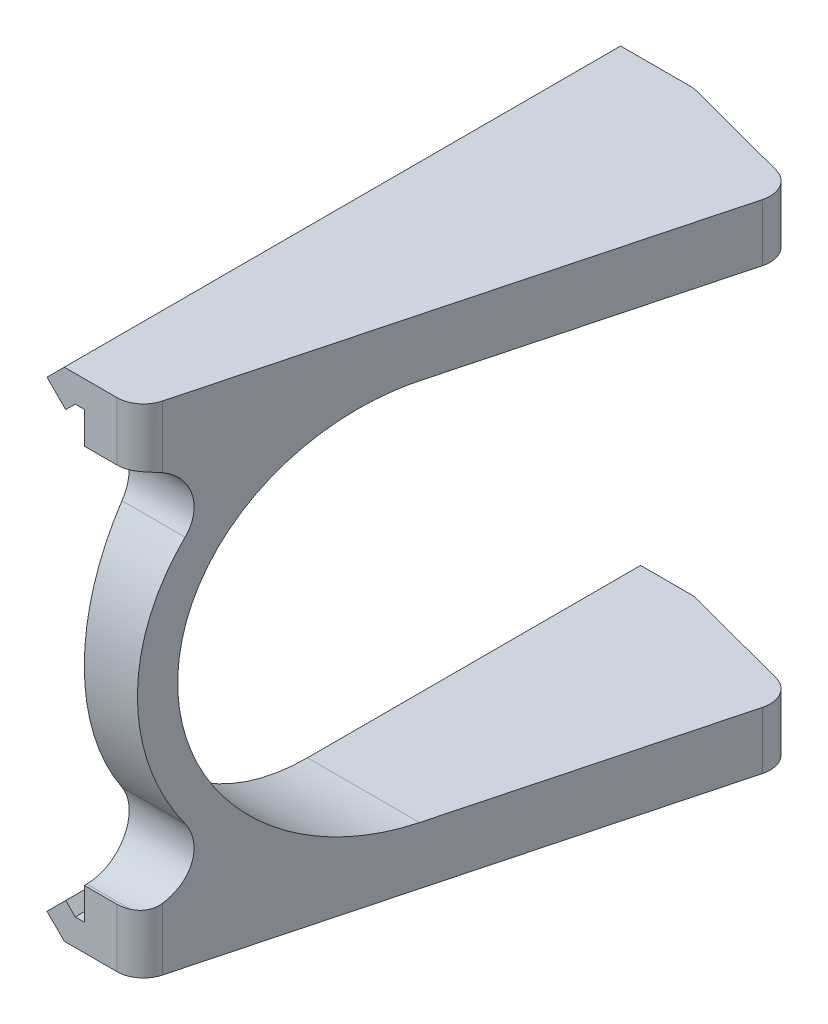
SolidWorks part; units mm, degrees
ref_plane "Front Plane" through (0, 0, 0) normal (0, 0, 1) x (1, 0, 0)
ref_plane "Top Plane" through (0, 0, 0) normal (0, 1, 0) x (1, 0, 0)
ref_plane "Right Plane" through (0, 0, 0) normal (1, 0, 0) x (0, 0, -1)
sketch "Sketch1" plane through (0, 0, 0) normal (0, 0, 1) x (1, 0, 0)
  line L0 (-68.2875, 96.7196) -> (-66.4875, 98.5196)
  line L1 (-66.4875, 98.5196) -> (-64.7875, 98.5196)
  line L2 (-64.7875, 98.5196) -> (-64.7875, 14.8821)
  line L8 (-54.7875, 9.8821) -> (-54.7875, 103.5196)
  line L9 (-54.7875, 103.5196) -> (-68.5586, 103.5196)
  line L10 (-68.5586, 103.5196) -> (-71.823, 100.2552)
  line L11 (-71.823, 100.2552) -> (-68.2875, 96.7196)
  line L12 (-64.7875, 74.7196) -> (-64.7875, 98.2196) construction
  line L13 (-66.7875, 98.2196) -> (-67.7875, 97.2196) construction
  line L14 (-66.7875, 98.2196) -> (-64.7875, 98.2196) construction
  line L15 (-67.7875, 97.2196) -> (-67.7875, 74.7196) construction
  line L16 (-64.7875, 56.7009) -> (-45.1184, 56.7009) construction
  line L17 (-71.823, 13.1466) -> (-68.2875, 16.6821)
  line L18 (-68.2875, 16.6821) -> (-66.4875, 14.8821)
  line L19 (-68.5586, 9.8821) -> (-71.823, 13.1466)
  line L20 (-54.7875, 9.8821) -> (-68.5586, 9.8821)
  line L21 (-66.4875, 14.8821) -> (-64.7875, 14.8821)
  line L22 (-66.7875, 15.1821) -> (-67.7875, 16.1821) construction
  dimension "D1" = 10
  dimension "D2" = 5
  dimension "D3" = 0.3
  dimension "D4" = 5
  dimension "D5" = 0.5
extrude "Boss-Extrude1" add sketch "Sketch1" along normal up to surface (91.9928 mm away) and the other way up to surface (12.7822 mm away)
sketch "Sketch2" plane through (0, 9.8821, 0) normal (0, 1, 0) x (1, 0, 0)
  line L0 (-54.7875, 12.7822) -> (-54.7875, -91.9928)
  line L1 (-54.7875, -91.9928) -> (-28.8809, 5.9282)
  line L2 (-28.8809, 5.9282) -> (-54.7875, 12.7822)
  dimension "D1" = 14.819
extrude "Boss-Extrude2" add sketch "Sketch2" along direction (0, -1, 0) on the side of the normal up to surface (93.6375 mm away)
sketch "Sketch3" plane through (-64.7875, 0, 0) normal (-1, 0, 0) x (0, 0, 1)
  line L0 (-12.7822, 56.7009) -> (91.9928, 56.7009) construction
  line L1 (-12.7822, 14.8821) -> (-12.7822, 98.5196) construction
  line L2 (91.9928, 14.8821) -> (91.9928, 98.5196) construction
  line L3 (66.6574, 20.6821) -> (52.8488, 20.6821) construction
  line L4 (49.974, 92.7196) -> (-12.7822, 92.7196)
  line L5 (-12.7822, 92.7196) -> (-12.7822, 20.6821)
  line L6 (-12.7822, 20.6821) -> (49.974, 20.6821)
  line L8 (85.9928, 52.4105) -> (85.9928, 59.8544) construction
  line L9 (91.5431, 20.8821) -> (97.1802, 20.8821)
  line L10 (97.1802, 20.8821) -> (97.1802, 92.5196)
  line L11 (91.9928, 14.8821) -> (-12.7822, 14.8821) construction
  line L13 (91.5431, 92.5196) -> (97.1802, 92.5196)
  arc A0 (49.974, 20.6821) -> (49.974, 92.7196) centre (49.974, 56.7009) ccw
  arc A1 (84.8946, 80.0703) -> (84.8946, 33.3315) centre (49.974, 56.7009) cw
  arc A2 (84.8946, 33.3315) -> (91.5431, 20.8821) centre (91.5431, 28.8821) ccw
  arc A3 (84.8946, 80.0703) -> (91.5431, 92.5196) centre (91.5431, 84.5196) cw
  point P23 (84.4864, 25.1135)
  dimension "D1" = 6
  dimension "D2" = 6
  dimension "D3" = 8
extrude "Cut-Extrude1" cut sketch "Sketch3" against normal through all
fillet "Fillet1" radius 5 6 edges at (-54.7875, 15.2821, -12.7822) (-54.7875, 98.1196, -12.7822) (-28.8809, 15.2821, -5.9282) (-28.8809, 98.1196, -5.9282) (-54.7875, 15.3821, 91.9928) (-54.7875, 98.0196, 91.9928)
equation "\"angle\" = 14.819"
